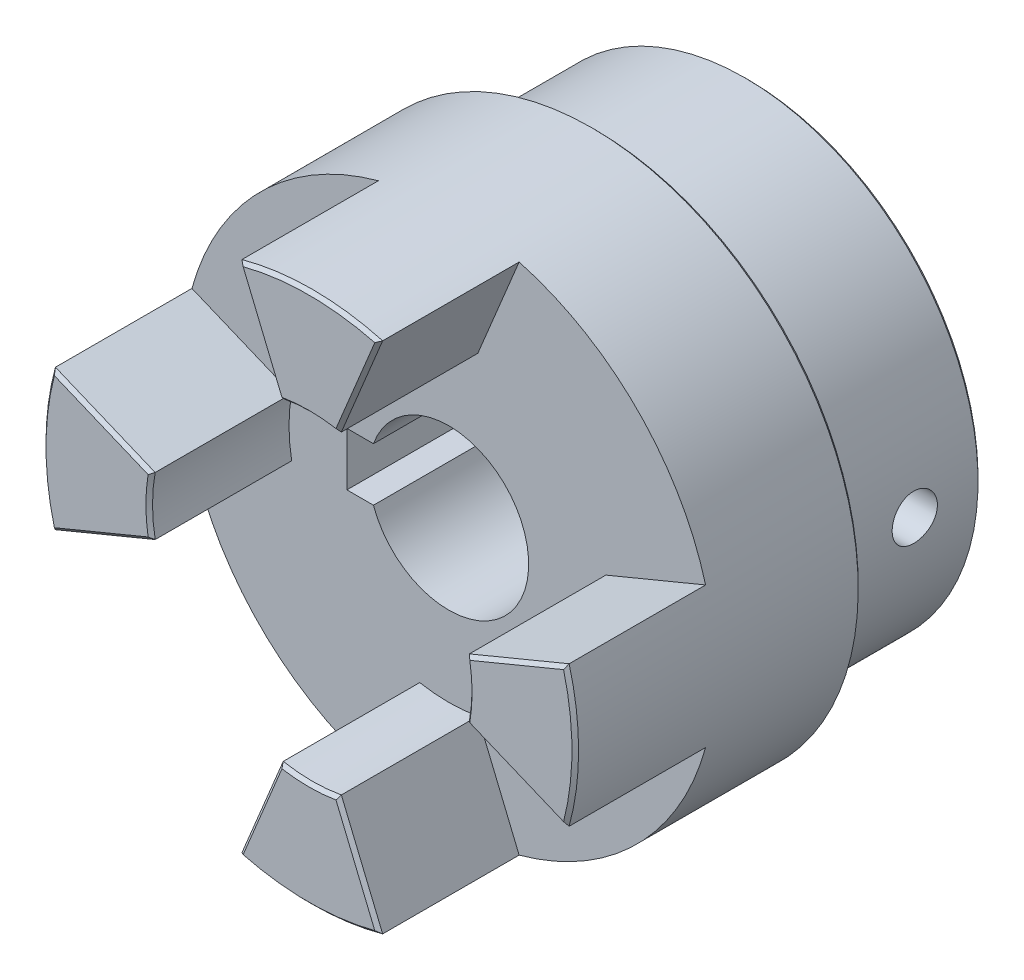
SolidWorks part; units mm, degrees
material "1060 Alloy"
ref_plane "Front Plane" through (0, 0, 0) normal (0, 0, 1) x (1, 0, 0)
ref_plane "Top Plane" through (0, 0, 0) normal (0, 1, 0) x (1, 0, 0)
ref_plane "Right Plane" through (0, 0, 0) normal (1, 0, 0) x (0, 0, -1)
sketch "Sketch1" plane through (0, 0, 0) normal (1, 0, 0) x (0, 0, -1)
  line L0 (0, 0) -> (-62.4415, 0) construction
  line L1 (0, 35) -> (0, 12)
  line L2 (0, 12) -> (-45, 12)
  line L3 (0, 35) -> (-23, 35)
  line L4 (-23, 35) -> (-23, 40)
  line L5 (-23, 40) -> (-45, 40)
  line L8 (-45, 40) -> (-45, 12)
  dimension "D1" = 24
  dimension "D2" = 22
  dimension "D3" = 70
  dimension "D4" = 80
  dimension "D5" = 23
revolve "Revolve1" add sketch "Sketch1" angle 360 about L0
sketch "Sketch3" plane through (0, 0, 45) normal (0, 0, 1) x (1, 0, 0)
  line L0 (0, 0) -> (0, 56.5428) construction
  line L1 (4.365, 23.5997) -> (10.5694, 38.5783)
  line L2 (-4.365, 23.5997) -> (-10.5694, 38.5783)
  line L3 (-4.365, 23.5997) -> (4.365, 23.5997)
  arc A0 (4.365, 23.5997) -> (-4.365, 23.5997) centre (0, 0) ccw
  arc A1 (10.5694, 38.5783) -> (-10.5694, 38.5783) centre (0, 0) ccw
  point P3 (0, 23.5997)
  circle M6 centre (0, 0) radius 40
  dimension "D1" = 48
  dimension "D2" = 45
  dimension "D3" = 22.5
  dimension "D4" = 22.5
  dimension "D5" = 8.73
extrude "Boss-Extrude1" add sketch "Sketch3" along normal blind 21 contours A0 L0 A1 L2 | L0 A0 L1 M6
pattern_circular "CirPattern1" count 4 over 360 about axis through (0, 0, 0) along (0, 0, 1) of "Boss-Extrude1"
chamfer "Chamfer1" distance 0.5 angle 45 16 edges at (0, 24, 66) (-7.4672, 31.089, 66) (7.4672, 31.089, 66) (0, 40, 66) (24, 0, 66) (31.089, 7.4672, 66) (31.089, -7.4672, 66) (40, 0, 66) (0, -24, 66) (7.4672, -31.089, 66) (-7.4672, -31.089, 66) (0, -40, 66) (-24, 0, 66) (-31.089, -7.4672, 66) (-31.089, 7.4672, 66) (-40, 0, 66)
sketch "Sketch4" plane through (0, 0, 45) normal (0, 0, 1) x (1, 0, 0)
  line L1 (-15.3, -4) -> (-8.7, -4)
  line L2 (-15.3, -4) -> (-15.3, 4)
  line L3 (-15.3, 4) -> (-8.7, 4)
  line L4 (-8.7, -4) -> (-8.7, 4)
  line L5 (-15.3, -4) -> (-8.7, 4) construction
  line L6 (-15.3, 4) -> (-8.7, -4) construction
  circle A0 centre (0, 0) radius 12 construction
  point P0 (-12, 0)
  point P8 (0, 0)
  dimension "D1" = 8
  dimension "D2" = 15.3
extrude "Cut-Extrude1" cut sketch "Sketch4" against normal through all
chamfer "Chamfer2" distance 0.5 angle 45 2 edges at (0, 40, 23) (0, 35, 0)
fillet "Fillet1" radius 1 1 edges at (0, 35, 23)
hole_wizard "M8x1.25 Tapped Hole1" positions "Sketch5" profile "Sketch6" tap size "M8x1.25" standard "ANSI Metric"
sketch "Sketch5" plane through (0, 0, 0) normal (1, 0, 0) x (0, 0, -1)
  point P0 (-10, 0)
  dimension "D1" = 10
sketch "Sketch6" plane through (0, 0, 10) normal (0, 1, 0) x (0, 0, 1)
  line L0 (0, 0) -> (0, 40)
  line L1 (0, 40) -> (3.4, 40)
  line L2 (3.4, 40) -> (3.4, 0)
  line L5 (3.4, 0) -> (0, 0)
  line L11 (0, -6.35) -> (0, 107.95) construction
  dimension "Thru Tap Drill Dia." = 6.8
  dimension "Thru Tap Drill Depth" = 40
cosmetic thread "Hole Thread1" parameters "D2"=8
pattern_circular "CirPattern4" count 4 over 360 about axis through (0, 0, 0) along (0, 0, -1) skipping 1, 2 of "M8x1.25 Tapped Hole1"
cosmetic thread "Hole Thread2" parameters "D2"=8
